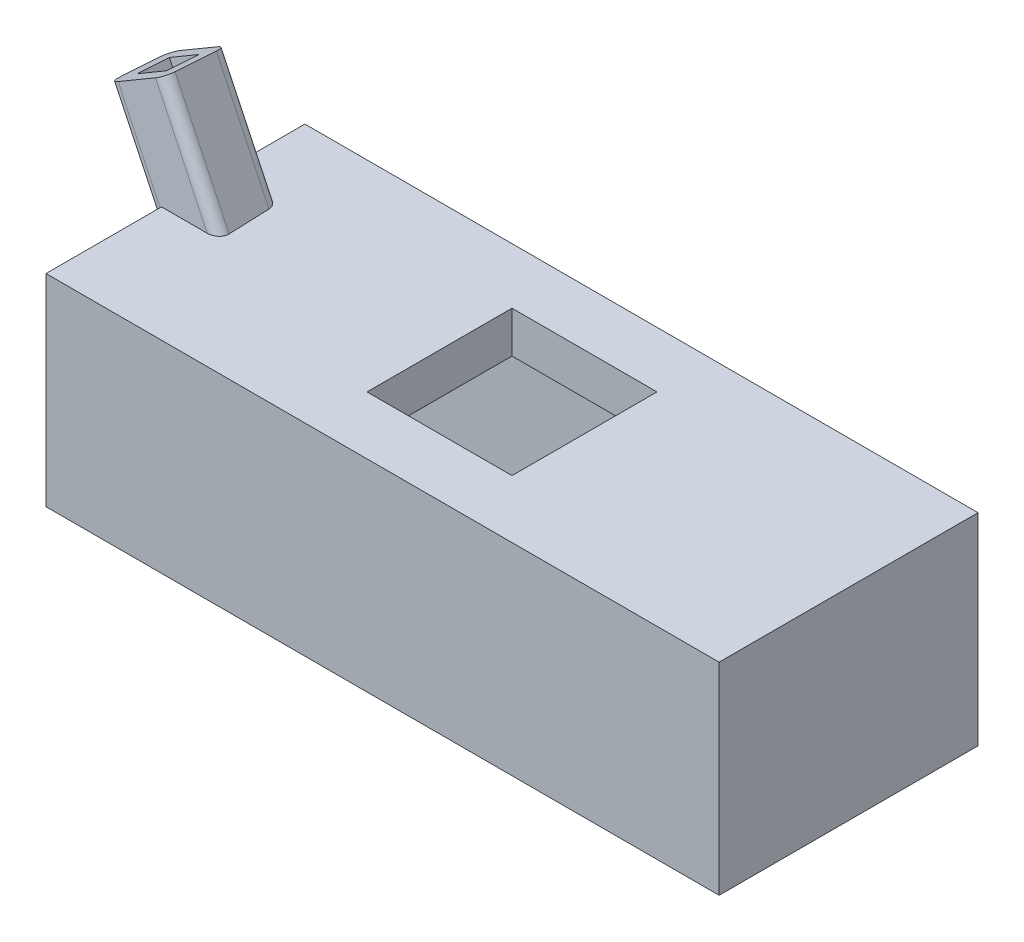
SolidWorks part; units mm, degrees
ref_plane "Alzado" through (0, 0, 0) normal (0, 0, 1) x (1, 0, 0)
ref_plane "Planta" through (0, 0, 0) normal (0, 1, 0) x (1, 0, 0)
ref_plane "Vista lateral" through (0, 0, 0) normal (1, 0, 0) x (0, 0, -1)
sketch "Croquis1" plane through (0, 0, 0) normal (0, 1, 0) x (1, 0, 0)
  line L1 (9.5, -9.5) -> (-9.5, -9.5)
  line L2 (9.5, -9.5) -> (9.5, 9.5)
  line L3 (9.5, 9.5) -> (-9.5, 9.5)
  line L4 (-9.5, -9.5) -> (-9.5, 9.5)
  line L5 (9.5, -9.5) -> (-9.5, 9.5) construction
  line L6 (9.5, 9.5) -> (-9.5, -9.5) construction
  point P0 (0, 0)
  dimension "D1" = 19
  dimension "D2" = 19
extrude "Saliente-Extruir1" add sketch "Croquis1" along normal blind 4
sketch "Croquis2" plane through (0, 4, 0) normal (0, 1, 0) x (1, 0, 0)
  line L0 (-9.5, -9.5) -> (9.5, -9.5) construction
  line L1 (6.25, -5.5) -> (-7.75, -5.5)
  line L2 (6.25, -5.5) -> (6.25, 8.5)
  line L3 (6.25, 8.5) -> (-7.75, 8.5)
  line L4 (-7.75, -5.5) -> (-7.75, 8.5)
  line L5 (6.25, -5.5) -> (-7.75, 8.5) construction
  line L6 (6.25, 8.5) -> (-7.75, -5.5) construction
  line L7 (9.5, -9.5) -> (9.5, 9.5) construction
  point P0 (-0.75, 1.5)
  point P5 (1.1506, 1.6465)
  dimension "D1" = 14
  dimension "D2" = 14
  dimension "D3" = 4
  dimension "D4" = 3.25
extrude "Cortar-Extruir1" cut sketch "Croquis2" against normal blind 4
sketch "Croquis3" plane through (0, 4, 0) normal (0, 1, 0) x (1, 0, 0)
  line L0 (-9.5, 9.5) -> (-31.5, 5.7308)
  line L1 (-9.5, -2.5) -> (-31.5, 0.051)
  line L2 (-9.5, 9.5) -> (-9.5, -9.5) construction
  line L3 (-9.5, -2.5) -> (-9.5, 9.5)
  line L4 (-31.5, 5.7308) -> (-31.5, 0.051)
  line L5 (-9.5, -9.5) -> (9.5, -9.5) construction
  point P7 (0, 0)
  point P9 (0, 0)
  dimension "D2" = 22
  dimension "D1" = 7
  dimension "D3" = 9.551
  dimension "D4" = 3.7692
extrude "Saliente-Extruir2" add sketch "Croquis3" against normal blind 4
sketch "Croquis8" plane through (-0.4121, 0, 3.5538) normal (-0.1152, 0, 0.9933) x (0.9933, 0, 0.1152)
  line L0 (-31.2962, 4) -> (-36.2962, 12.6603) construction
  line L1 (-31.2962, 4) -> (-9.1488, 4) construction
  line L2 (-34.3173, 13.8028) -> (-40.2544, 10.375) construction
  dimension "D1" = 60
  dimension "D2" = 10
ref_plane "Plano2" through (-14.4592, 25.2119, -1.6766) normal (-0.4967, 0.866, -0.0576) x (0.8679, 0.4956, -0.033)
sketch "Croquis9" plane through (-14.4592, 25.2119, -1.6766) normal (-0.4967, 0.866, -0.0576) x (0.8679, 0.4956, -0.033)
  line L0 (-25.3561, -0.2145) -> (-24.9544, 2.7855) construction
  line L5 (-23.0913, -0.5177) -> (-29.8862, 0.3921) construction
  line L7 (-27.9544, -0.2145) -> (-21.9544, -0.2145)
  line L8 (-27.9544, -0.2145) -> (-27.9544, 5.7855)
  line L9 (-27.9544, 5.7855) -> (-21.9544, 5.7855)
  line L10 (-21.9544, -0.2145) -> (-21.9544, 5.7855)
  line L11 (-27.9544, -0.2145) -> (-21.9544, 5.7855) construction
  line L12 (-27.9544, 5.7855) -> (-21.9544, -0.2145) construction
  dimension "D1" = 3
  dimension "D2" = 6
  dimension "D3" = 6
extrude "Saliente-Extruir6" add sketch "Croquis9" against normal blind 20
sketch "Croquis11" plane through (-14.4592, 25.2119, -1.6766) normal (-0.4967, 0.866, -0.0576) x (0.8679, 0.4956, -0.033)
  line L0 (-24.9544, 5.7855) -> (-24.9544, -0.2145) construction
  line L1 (-21.9544, 5.7855) -> (-27.9544, 5.7855) construction
  line L2 (-27.9544, -0.2145) -> (-21.9544, -0.2145) construction
  line L3 (-27.9544, 2.7855) -> (-21.9544, 2.7855) construction
  line L4 (-27.9544, 5.7855) -> (-27.9544, -0.2145) construction
  line L5 (-21.9544, -0.2145) -> (-21.9544, 5.7855) construction
  line L7 (-23.3794, 1.2105) -> (-26.5294, 1.2105)
  line L8 (-23.3794, 1.2105) -> (-23.3794, 4.3605)
  line L9 (-23.3794, 4.3605) -> (-26.5294, 4.3605)
  line L10 (-26.5294, 1.2105) -> (-26.5294, 4.3605)
  line L11 (-23.3794, 1.2105) -> (-26.5294, 4.3605) construction
  line L12 (-23.3794, 4.3605) -> (-26.5294, 1.2105) construction
  point P12 (-24.9544, 2.7855)
  dimension "D1" = 3.15
  dimension "D2" = 3.15
extrude "Cortar-Extruir3" cut sketch "Croquis11" against normal blind 20
fillet "Redondeo1" radius 3 3 edges at (-9.5, 2, 9.5) (9.5, 2, -9.5) (9.5, 2, 9.5)
fillet "Redondeo2" radius 3 1 edges at (-9.5, 2, -9.5)
fillet "Redondeo3" radius 3 1 edges at (-9.5, 2, 2.5)
fillet "Redondeo6" radius 1 5 edges at (-24.4338, -1.4872, 0.3139) (-24.5479, -1.6863, -5.6861) (-33.7552, 2.7123, 0.0346) (-30.6617, 8.974, -6.3951) (-30.5475, 9.173, -0.395)
fillet "Redondeo7" radius 1 1 edges at (-33.7552, 2.3142, -5.9522)
sketch "Croquis12" plane through (0, 4, 0) normal (0, 1, 0) x (1, 0, 0)
  line L0 (31.85, -11.1) -> (31.85, 13.9) construction
  line L1 (-33.15, -11.1) -> (31.85, -11.1)
  line L2 (-33.15, -11.1) -> (-33.15, 13.9)
  line L3 (-33.15, 13.9) -> (31.85, 13.9)
  line L4 (31.85, -11.1) -> (31.85, 13.9)
  line L6 (-17.15, 13.9) -> (-33.15, 13.9) construction
  line L7 (-33.15, 13.9) -> (-33.15, 4.4) construction
  line L8 (-7.75, -5.5) -> (6.25, -5.5) construction
  line L9 (6.25, -5.5) -> (6.25, 8.5) construction
  line L10 (6.25, 8.5) -> (-7.75, 8.5) construction
  line L11 (-7.75, 8.5) -> (-7.75, -5.5) construction
  line L12 (-7.75, -5.5) -> (6.25, -5.5)
  line L13 (6.25, -5.5) -> (6.25, 8.5)
  line L14 (6.25, 8.5) -> (-7.75, 8.5)
  line L15 (-7.75, 8.5) -> (-7.75, -5.5)
  point P7 (0, 0)
  point P8 (6.5, 9.5)
  point P10 (6.5, -9.5)
  point P11 (6.5, 9.5)
  point P12 (-33.15, -11.1)
  point P14 (-33.15, 13.9)
extrude "Saliente-Extruir7" add sketch "Croquis12" against normal up to surface (4 mm away)
sketch "Croquis13" plane through (0, 4, 0) normal (0, 1, 0) x (1, 0, 0)
  line L1 (31.85, -11.1) -> (-33.15, -11.1)
  line L2 (31.85, -11.1) -> (31.85, 13.9)
  line L3 (31.85, 13.9) -> (-33.15, 13.9)
  line L4 (-33.15, -11.1) -> (-33.15, 13.9)
  line L5 (29.35, -9.8) -> (-30.65, -9.8)
  line L6 (29.35, -9.8) -> (29.35, 12.6)
  line L7 (29.35, 12.6) -> (-30.65, 12.6)
  line L8 (-30.65, -9.8) -> (-30.65, 12.6)
  dimension "D1" = 2.5
  dimension "D2" = 1.3
  dimension "D3" = 1.3
  dimension "D4" = 2.5
extrude "Saliente-Extruir8" add sketch "Croquis13" against normal up to surface (19.5 mm away)
sketch "Croquis15" plane through (-14.4592, 25.2119, -1.6766) normal (-0.4967, 0.866, -0.0576) x (0.8679, 0.4956, -0.033)
  line L1 (-26.5294, 4.3605) -> (-23.3794, 4.3605)
  line L2 (-26.5294, 4.3605) -> (-26.5294, 1.2105)
  line L3 (-26.5294, 1.2105) -> (-23.3794, 1.2105)
  line L4 (-23.3794, 4.3605) -> (-23.3794, 1.2105)
extrude "Cortar-Extruir4" cut sketch "Croquis15" against normal up to surface (20 mm away) up to face at (-26.1846, -4.6603, -2.4817)
